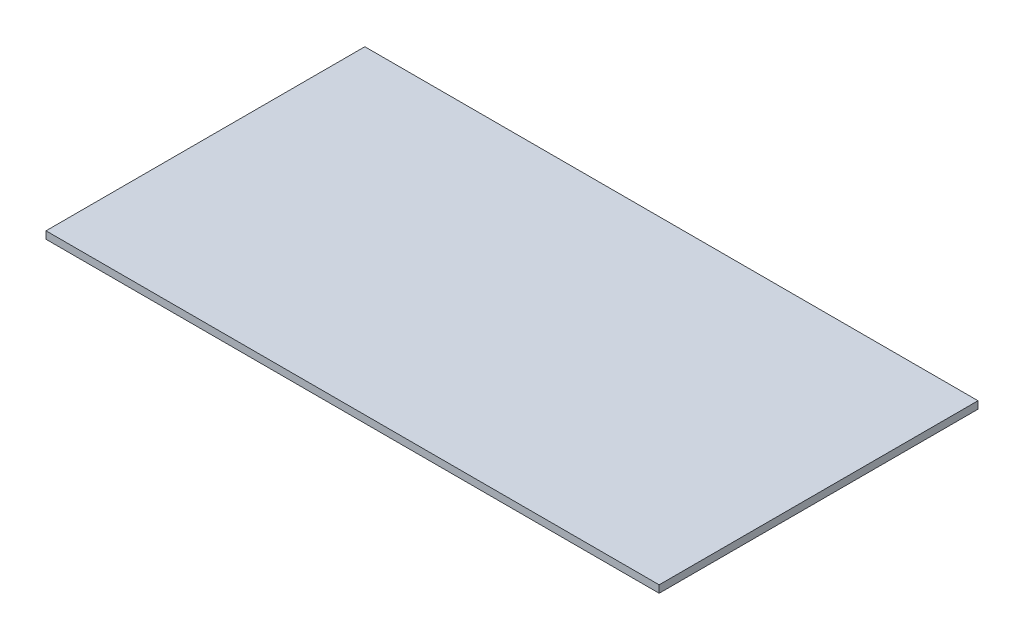
SolidWorks part; units mm, degrees
ref_plane "Front Plane" through (0, 0, 0) normal (0, 0, 1) x (1, 0, 0)
ref_plane "Top Plane" through (0, 0, 0) normal (0, 1, 0) x (1, 0, 0)
ref_plane "Right Plane" through (0, 0, 0) normal (1, 0, 0) x (0, 0, -1)
sketch "Sketch1" plane through (0, 0, 0) normal (0, 1, 0) x (1, 0, 0)
  line L1 (-125, 65) -> (125, 65)
  line L2 (-125, 65) -> (-125, -65)
  line L3 (-125, -65) -> (125, -65)
  line L4 (125, 65) -> (125, -65)
  line L5 (-125, 65) -> (125, -65) construction
  line L6 (-125, -65) -> (125, 65) construction
  point P0 (0, 0)
  dimension "D1" = 130
  dimension "D2" = 250
extrude "Boss-Extrude1" add sketch "Sketch1" along normal blind 3
